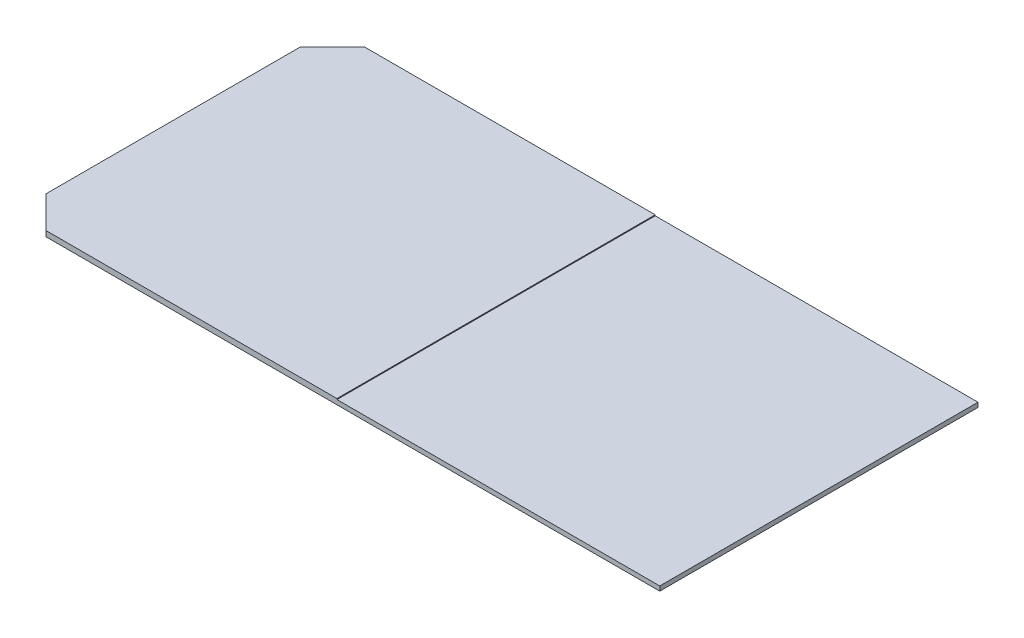
SolidWorks part; units mm, degrees
ref_plane "Front Plane" through (0, 0, 0) normal (0, 0, 1) x (1, 0, 0)
ref_plane "Top Plane" through (0, 0, 0) normal (0, 1, 0) x (1, 0, 0)
ref_plane "Right Plane" through (0, 0, 0) normal (1, 0, 0) x (0, 0, -1)
sketch "Sketch1" plane through (0, 0, 0) normal (0, 1, 0) x (1, 0, 0)
  line L1 (0, 0) -> (710, 0)
  line L2 (0, 0) -> (0, 350)
  line L3 (0, 350) -> (710, 350)
  line L4 (710, 0) -> (710, 350)
  dimension "D1" = 710
  dimension "D2" = 350
extrude "Boss-Extrude1" add sketch "Sketch1" along normal blind 5
sketch "Sketch2" plane through (0, 5, 0) normal (0, 1, 0) x (1, 0, 0)
  line L0 (710, 350) -> (0, 350) construction
  line L1 (355, 350) -> (355, 0)
  line L2 (0, 0) -> (710, 0) construction
  line L7 (0, 350) -> (0, 0)
  line L8 (0, 0) -> (710, 0)
  line L9 (710, 0) -> (710, 350)
  line L10 (710, 350) -> (0, 350)
  line L11 (0, 350) -> (0, 0)
  line L12 (0, 0) -> (710, 0)
  line L13 (710, 0) -> (710, 350)
  line L14 (710, 350) -> (0, 350)
  point P6 (0, 0)
  line M5 (0, 350) -> (0, 0)
  line M6 (0, 0) -> (710, 0)
  line M8 (710, 350) -> (0, 350)
  dimension "D1" = 0
extrude "Boss-Extrude2" add sketch "Sketch2" along normal blind 1 contours L1 M8 M5 M6
sketch "Sketch3" plane through (0, 6, 0) normal (0, 1, 0) x (1, 0, 0)
  line L0 (0, 315) -> (35, 350)
  line L1 (0, 350) -> (0, 0) construction
  line L2 (355, 350) -> (0, 350) construction
  line L3 (0, 175) -> (821.6637, 175) construction
  line L4 (0, 35) -> (35, 0)
  line L9 (355, 0) -> (355, 350)
  line L10 (355, 350) -> (0, 350)
  line L11 (0, 350) -> (0, 0)
  line L12 (0, 0) -> (355, 0)
  line L13 (355, 0) -> (355, 350)
  line L14 (355, 350) -> (0, 350)
  line L15 (0, 350) -> (0, 0)
  line L16 (0, 0) -> (355, 0)
  line M8 (355, 350) -> (0, 350)
  line M9 (0, 350) -> (0, 0)
  line M10 (0, 0) -> (355, 0)
  dimension "D1" = 45
  dimension "D2" = 35
  dimension "D3" = 0
extrude "Cut-Extrude1" cut sketch "Sketch3" against normal through all contours L0 M9 M8 | L4 M9 M10
